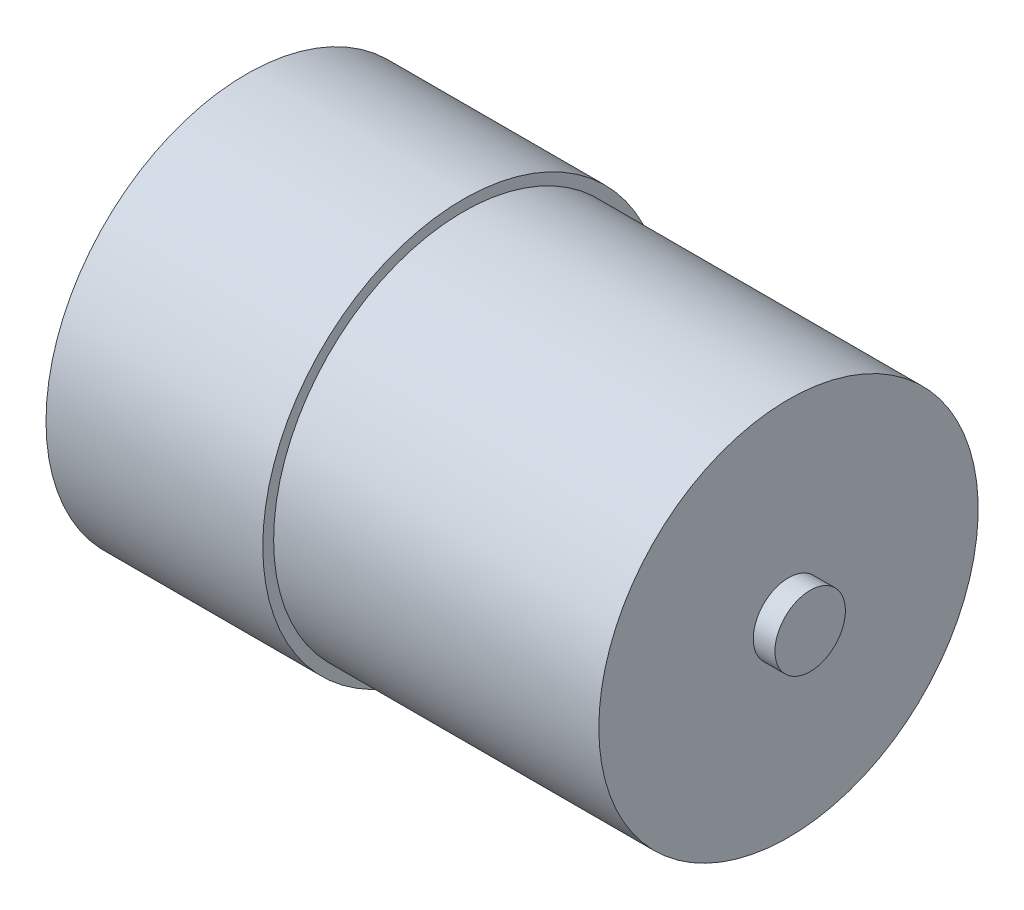
SolidWorks part; units mm, degrees
ref_plane "前视基准面" through (0, 0, 0) normal (0, 0, 1) x (1, 0, 0)
ref_plane "上视基准面" through (0, 0, 0) normal (0, 1, 0) x (1, 0, 0)
ref_plane "右视基准面" through (0, 0, 0) normal (1, 0, 0) x (0, 0, -1)
other "Configuration Table"
sketch "草图1" plane through (0, 0, 0) normal (0, 0, 1) x (1, 0, 0)
  line L0 (-72.035, 0) -> (69.3285, 0) construction
  line L3 (30, 12.2) -> (30, 3.25)
  line L4 (30.8583, 0) -> (0, 0)
  line L5 (30.8583, 0) -> (32, 0)
  line L6 (32, 0) -> (32, 3.25)
  line L7 (32, 3.25) -> (30, 3.25)
  line L8 (0, 0) -> (-19.9417, 0)
  line L9 (-20, 3.5) -> (-20, 18.5)
  line L10 (-20, 18.5) -> (0, 18.5)
  line L11 (-19.9417, 0) -> (-22.4417, 0)
  line L12 (-22.5, 2.1681) -> (-22.5, 3.5)
  line L13 (-22.5, 3.5) -> (-20, 3.5)
  line L17 (-31.4417, 0) -> (-22.4417, 0)
  line L18 (0, 0) -> (-19.9417, 0)
  line L20 (0, 0) -> (-19.9417, 0)
  line L21 (-31.4417, 0) -> (-31.4417, 2)
  line L22 (-31.4417, 2) -> (-22.4417, 2)
  line L23 (-22.4417, 2) -> (-22.5, 2.1681)
  line L24 (0, 18.5) -> (0, 17.5)
  line L25 (0, 17.5) -> (30, 17.5)
  line L26 (30, 17.5) -> (30, 12.2)
  point P4 (-21.25, 3.5)
  dimension "D1" = 17.5
  dimension "D2" = 20
  dimension "D3" = 18.5
  dimension "D4" = 30
  dimension "D5" = 2.5
  dimension "D6" = 9
  dimension "D7" = 2
  dimension "D8" = 3.25
  dimension "D9" = 2
  dimension "D10" = 3.5
revolve "旋转1" add sketch "草图1" angle 360 about L0
sketch "草图2" plane through (-20, 0, 0) normal (-1, 0, 0) x (0, 0, 1)
  circle A0 centre (0, 0) radius 15.5 construction
  circle A1 centre (15.5, 0) radius 1.5
  circle A2 centre (7.75, -13.4234) radius 1.5
  circle A3 centre (-7.75, -13.4234) radius 1.5
  circle A4 centre (-15.5, 0) radius 1.5
  circle A5 centre (-7.75, 13.4234) radius 1.5
  circle A6 centre (7.75, 13.4234) radius 1.5
  point P18 (0, 0)
  dimension "D1" = 3
  dimension "D2" = 6
extrude "切除-拉伸1" cut sketch "草图2" against normal blind 5
sketch "草图3" plane through (-31.4417, 0, 0) normal (-1, 0, 0) x (0, 0, 1)
  line L1 (-2.5497, 3.1575) -> (2.5774, 3.1575)
  line L2 (-2.5497, 3.1575) -> (-2.5497, 1.5)
  line L3 (-2.5497, 1.5) -> (2.5774, 1.5)
  line L4 (2.5774, 3.1575) -> (2.5774, 1.5)
  dimension "D1" = 1.5
extrude "切除-拉伸2" cut sketch "草图3" against normal blind 8
